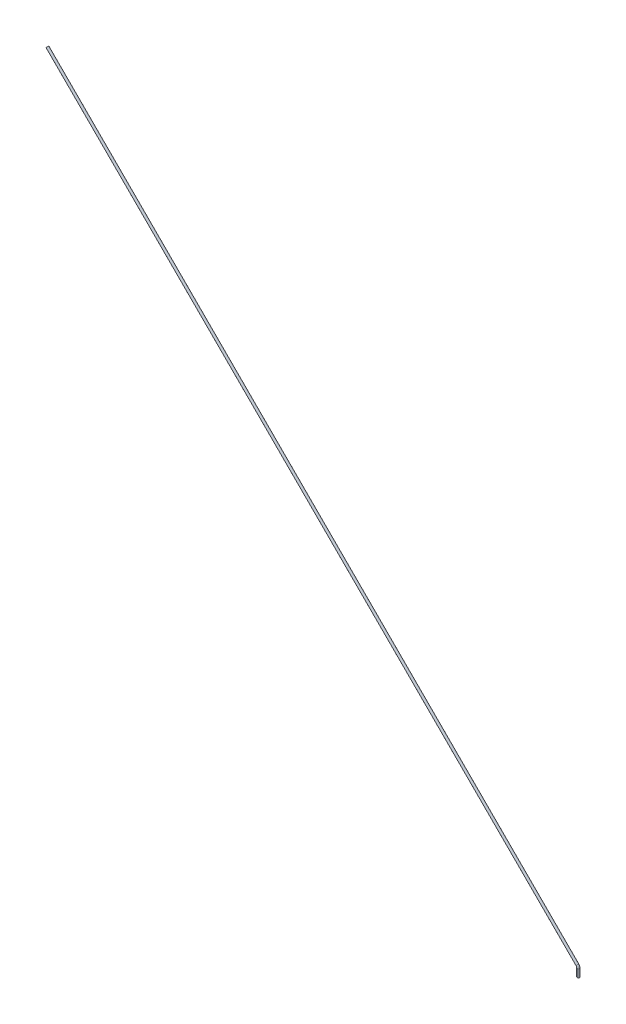
SolidWorks part; units mm, degrees
ref_plane "Front Plane" through (0, 0, 0) normal (0, 0, 1) x (1, 0, 0)
ref_plane "Top Plane" through (0, 0, 0) normal (0, 1, 0) x (1, 0, 0)
ref_plane "Right Plane" through (0, 0, 0) normal (1, 0, 0) x (0, 0, -1)
sketch "Sketch1" plane through (0, 0, 0) normal (0, 1, 0) x (1, 0, 0)
  circle A0 centre (0, 0) radius 0.25
  dimension "D1" = 0.5
sketch "Sketch2" plane through (0, 0, 0) normal (0, 0, 1) x (1, 0, 0)
  line L0 (0, 0) -> (0, 1.6893)
  line L1 (-0.2197, 2.2197) -> (-115.2584, 117.2584)
  arc A0 (0, 1.6893) -> (-0.2197, 2.2197) centre (-0.75, 1.6893) ccw
  point P6 (0, 2)
  dimension "D4" = 0.75
  dimension "D1" = 45
  dimension "D2" = 2
  dimension "D3" = 163
sweep "Sweep1" add profiles "Sketch1" path "Sketch2"
